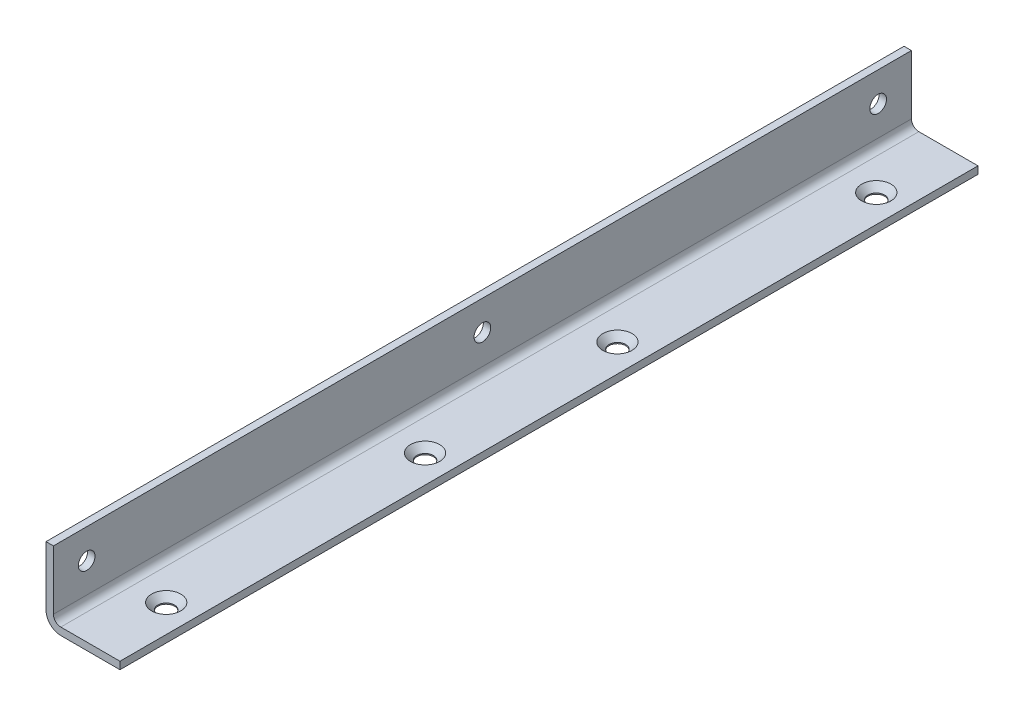
SolidWorks part; units mm, degrees
ref_plane "Спереди" through (0, 0, 0) normal (0, 0, 1) x (1, 0, 0)
ref_plane "Сверху" through (0, 0, 0) normal (0, 1, 0) x (1, 0, 0)
ref_plane "Справа" through (0, 0, 0) normal (1, 0, 0) x (0, 0, -1)
sketch "Эскиз1" plane through (0, 0, 0) normal (0, 0, 1) x (1, 0, 0)
  line L1 (0, 0) -> (20, 0)
  line L2 (0, 0) -> (0, 20)
  line L3 (0, 20) -> (2, 20)
  line L4 (20, 0) -> (20, 2)
  line L5 (4, 2) -> (20, 2)
  line L6 (2, 4) -> (2, 20)
  arc A0 (4, 2) -> (2, 4) centre (4, 4) cw
  dimension "D5" = 2
  dimension "D1" = 20
  dimension "D2" = 20
  dimension "D3" = 2
  dimension "D4" = 2
extrude "Вытянуть1" add sketch "Эскиз1" along normal blind 232
sketch "Эскиз2" plane through (2, 0, 0) normal (1, 0, 0) x (0, 0, -1)
  line L1 (-116, 12) -> (-116, 92.714) construction
  line L2 (-232, 4) -> (-232, 20) construction
  line L3 (-280.1291, 12) -> (26.6955, 12) construction
  line L4 (-232, 20) -> (0, 20) construction
  line L5 (0, 4) -> (0, 20) construction
  circle A0 centre (-223, 12) radius 2.25
  circle A1 centre (-9, 12) radius 2.25
  circle A2 centre (-116, 12) radius 2.25
  dimension "D2" = 4.5
  dimension "D5" = 107
  dimension "D4" = 214
  dimension "D1" = 8
extrude "Вырез-Вытянуть1" cut sketch "Эскиз2" against normal blind 10
sketch "Эскиз3" plane through (0, 2, 0) normal (0, 1, 0) x (1, 0, 0)
  line L0 (-101.7059, -116) -> (103.8615, -116) construction
  line L1 (20, 0) -> (4, 0) construction
  line L2 (20, -232) -> (4, -232) construction
  line L4 (12.5, -212) -> (12.5, -20) construction
  line L5 (20, -232) -> (20, 0) construction
  circle A1 centre (12.5, -212) radius 2.25
  circle A2 centre (12.5, -142) radius 2.25
  circle A5 centre (12.5, -20) radius 2.25
  circle A8 centre (12.5, -90) radius 2.25
  dimension "D1" = 70
  dimension "D2" = 4.5
  dimension "D3" = 7.5
  dimension "D4" = 52
extrude "Вырез-Вытянуть2" cut sketch "Эскиз3" against normal blind 10
chamfer "Фаска1" distance 1.7 angle 45 4 edges at (12.5, 2, 17.75) (12.5, 2, 92.25) (12.5, 2, 139.75) (12.5, 2, 214.25)
fillet "Скругление1" radius 4 1 edges at (0, 0, 116)
